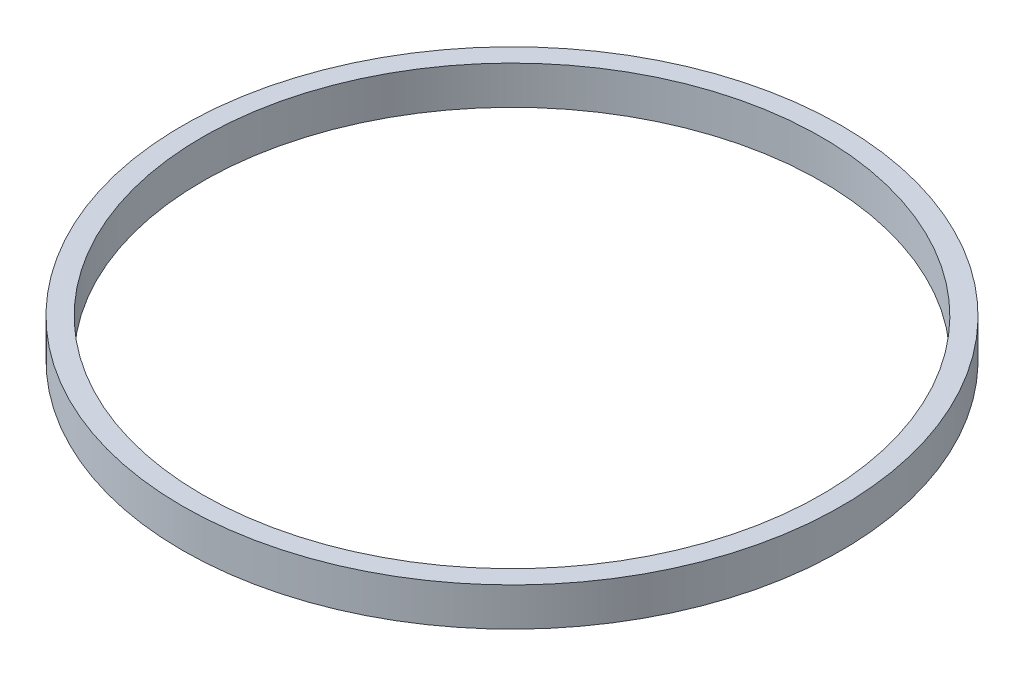
SolidWorks part; units mm, degrees
ref_plane "Front Plane" through (0, 0, 0) normal (0, 0, 1) x (1, 0, 0)
ref_plane "Top Plane" through (0, 0, 0) normal (0, 1, 0) x (1, 0, 0)
ref_plane "Right Plane" through (0, 0, 0) normal (1, 0, 0) x (0, 0, -1)
sketch "Sketch1" plane through (0, 0, 0) normal (0, 1, 0) x (1, 0, 0)
  circle A0 centre (0, 0) radius 20.2
  circle A1 centre (0, 0) radius 21.5
  dimension "D1" = 43
  dimension "D2" = 40.4
extrude "Boss-Extrude1" add sketch "Sketch1" along normal blind 2.5
